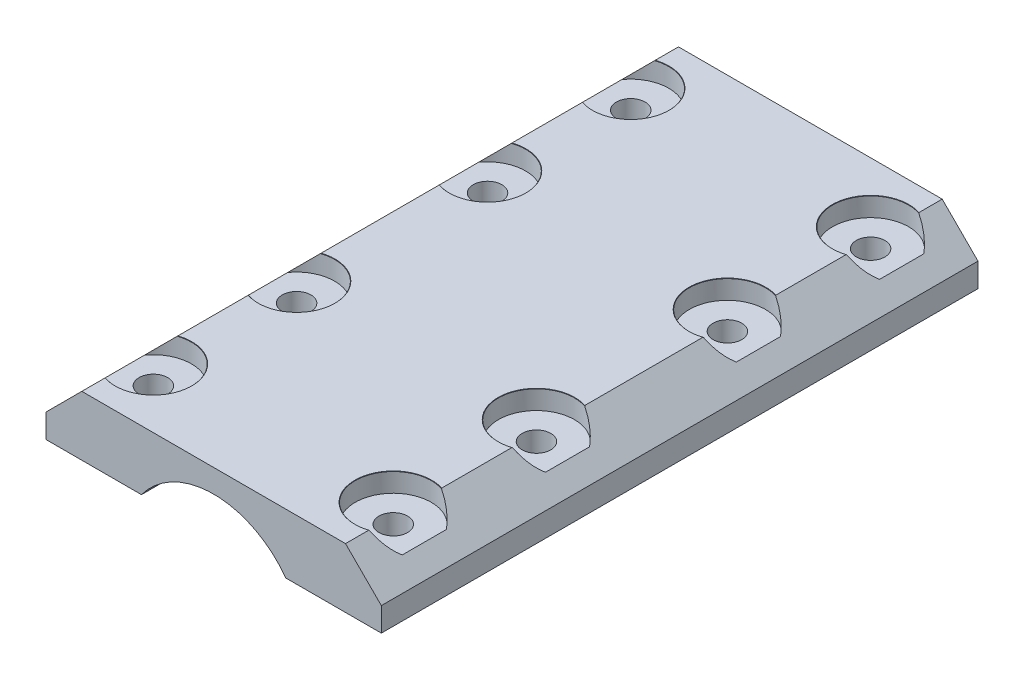
SolidWorks part; units mm, degrees
material "PLA"
ref_plane "Front Plane" through (0, 0, 0) normal (0, 0, 1) x (1, 0, 0)
ref_plane "Top Plane" through (0, 0, 0) normal (0, 1, 0) x (1, 0, 0)
ref_plane "Right Plane" through (0, 0, 0) normal (1, 0, 0) x (0, 0, -1)
sketch "Croquis1" plane through (0, 0, 0) normal (0, 0, 1) x (1, 0, 0)
  line L0 (0, 0) -> (8, 0)
  line L1 (0, 5) -> (28.1, 5)
  line L2 (20.1, 0) -> (28.1, 0)
  line L3 (0, 0) -> (0, 5)
  line L4 (28.1, 0) -> (28.1, 5)
  arc A1 (20.1, 0) -> (8, 0) centre (14.05, -4.43) ccw
  dimension "D1" = 7.4985
  dimension "D2" = 5
  dimension "D3" = 8
extrude "Saliente-Extruir1" add sketch "Croquis1" along normal blind 50
chamfer "Chaflán2" distance 3 angle 45 2 edges at (28.1, 5, 25) (0, 5, 25)
sketch "Croquis2" plane through (0, 5, 0) normal (0, 1, 0) x (1, 0, 0)
  point P4 (4, -5)
  point P5 (4, -17)
  point P6 (24.1, -17)
  point P7 (24.1, -5)
  point P9 (4, -33)
  point P10 (24.1, -33)
  point P11 (24.1, -45)
  point P12 (4, -45)
  dimension "D1" = 2
  dimension "D2" = 2
hole_wizard "CBORE for M2 Hex Head Machine Screw1" positions "Croquis2" profile "Croquis3" counterbore size "M2" standard "ANSI Metric"
sketch "Croquis3" plane through (4, 5, 5) normal (1, 0, 0) x (0, 0, 1)
  line L0 (0, 0) -> (0, 7)
  line L1 (0, 7) -> (1.2, 6.279)
  line L2 (1.2, 6.279) -> (1.2, 1.6)
  line L3 (1.2, 1.6) -> (3.19, 1.6)
  line L5 (3.19, 1.6) -> (3.19, 0.025)
  line L6 (3.19, 0.025) -> (3.215, 0)
  line L7 (3.215, 0) -> (0, 0)
  line L8 (-3.19, 0.025) -> (-3.215, 0) construction
  line L10 (0, 7) -> (-1.2, 6.279) construction
  line L11 (0, -6.35) -> (0, 107.95) construction
  dimension "Hole Dia." = 2.4
  dimension "Hole Depth" = 7
  dimension "C'Bore Dia." = 6.38
  dimension "C'Bore Depth" = 1.6
  dimension "Near C'Sink Dia." = 6.43
  dimension "Near C'Sink Angle" = 90
  dimension "Drill Angle" = 118
